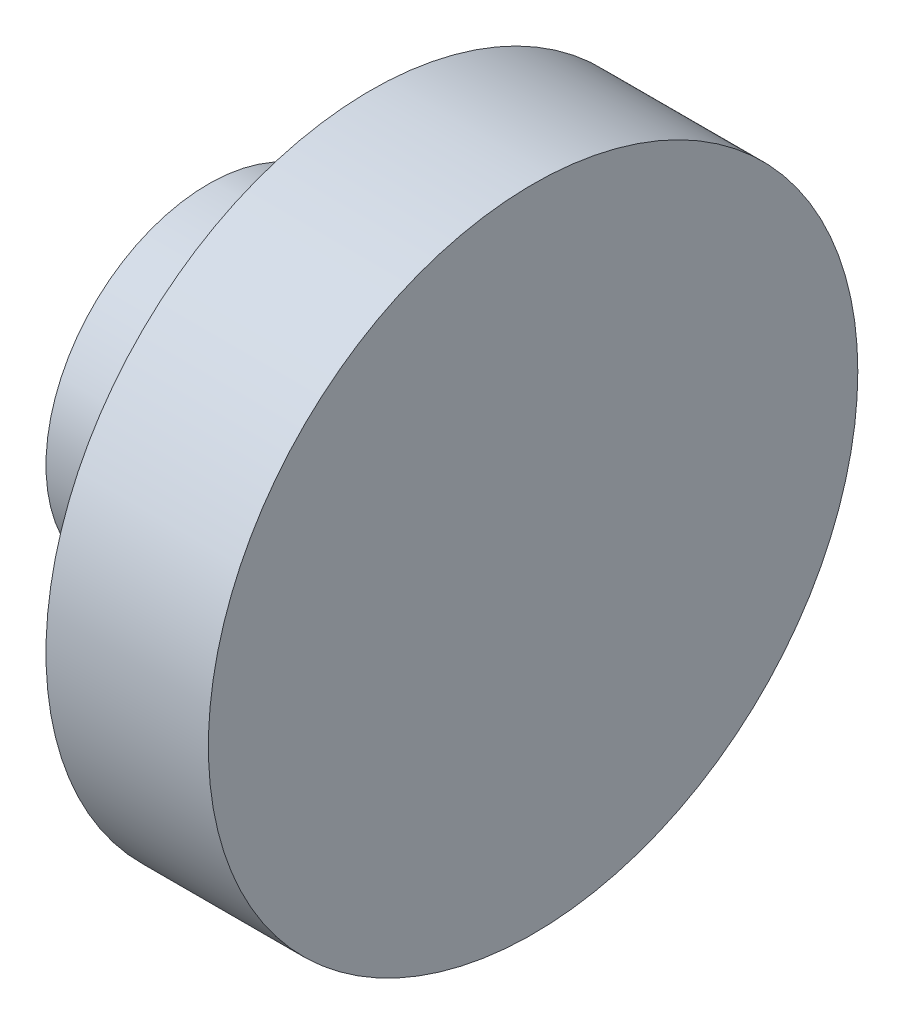
SolidWorks part; units mm, degrees
ref_plane "Front Plane" through (0, 0, 0) normal (0, 0, 1) x (1, 0, 0)
ref_plane "Top Plane" through (0, 0, 0) normal (0, 1, 0) x (1, 0, 0)
ref_plane "Right Plane" through (0, 0, 0) normal (1, 0, 0) x (0, 0, -1)
sketch "Sketch2" plane through (0, 0, 0) normal (0, 0, 1) x (1, 0, 0)
  line L0 (0, 0) -> (0, 6.35)
  line L1 (0, 6.35) -> (6.35, 6.35)
  line L2 (6.35, 6.35) -> (6.35, 12.7)
  line L3 (6.35, 12.7) -> (12.7, 12.7)
  line L4 (12.7, 12.7) -> (12.7, 0)
  line L5 (55, 0) -> (-55, 0) construction
  line L6 (12.7, 0) -> (0, 0)
  dimension "D1" = 6.35
  dimension "D2" = 12.7
  dimension "D3" = 6.35
  dimension "D4" = 6.35
revolve "Revolve1" add sketch "Sketch2" angle 360 about L6
hole_wizard "1/4-20 Tapped Hole1" positions "Sketch3" profile "Sketch5" tap size "1/4-20" standard "ANSI Inch"
sketch "Sketch3" plane through (0, 0, 0) normal (1, 0, 0) x (0, 0, -1)
  point P0 (0, 0)
sketch "Sketch5" plane through (0, 0, 0) normal (0, 1, 0) x (0, 0, 1)
  line L0 (0, 0) -> (0, 9.1538)
  line L1 (0, 9.1538) -> (2.5527, 7.62)
  line L2 (2.5527, 7.62) -> (2.5527, 0)
  line L5 (2.5527, 0) -> (0, 0)
  line L10 (0, 9.1538) -> (-2.5527, 7.62) construction
  line L11 (0, -6.35) -> (0, 107.95) construction
  dimension "Tap Drill Dia." = 5.1054
  dimension "Tap Drill Depth" = 7.62
  dimension "Drill Angle" = 118
cosmetic thread "Hole Thread1"
